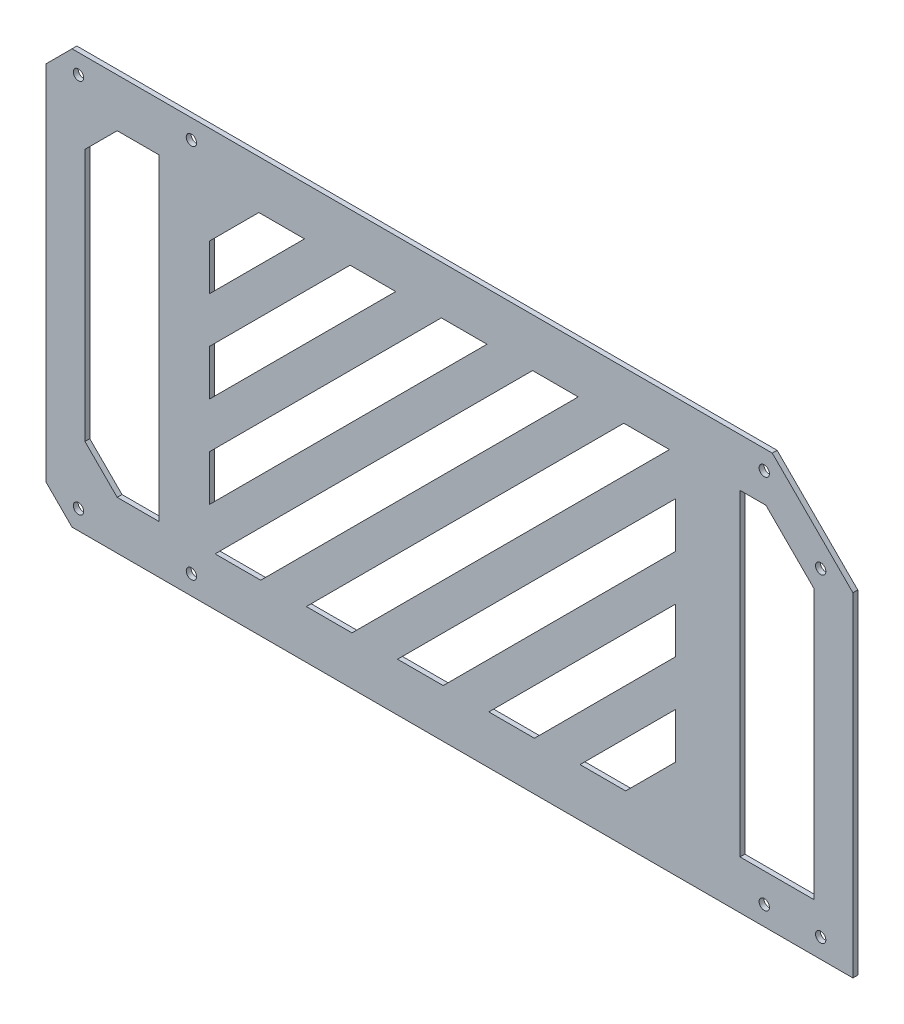
SolidWorks part; units mm, degrees
material "Thornel Mat VMA"
ref_plane "Front Plane" through (0, 0, 0) normal (0, 0, 1) x (1, 0, 0)
ref_plane "Top Plane" through (0, 0, 0) normal (0, 1, 0) x (1, 0, 0)
ref_plane "Right Plane" through (0, 0, 0) normal (1, 0, 0) x (0, 0, -1)
sketch "Sketch2" plane through (0, 0, 0) normal (0, 0, 1) x (1, 0, 0)
  line L0 (613.414, 102.9147) -> (613.414, 4.5) construction
  line L1 (613.414, 4.5) -> (600.414, 4.5) construction
  line L2 (600.414, 4.5) -> (590.414, 14.5) construction
  line L3 (590.414, 14.5) -> (590.414, 92.9147) construction
  line L4 (590.414, 92.9147) -> (600.414, 102.9147) construction
  line L5 (600.414, 102.9147) -> (613.414, 102.9147) construction
  line L6 (613.414, 102.9147) -> (613.414, 4.5)
  line L7 (613.414, 4.5) -> (600.414, 4.5)
  line L8 (600.414, 4.5) -> (590.414, 14.5)
  line L9 (785.4778, 117.9147) -> (785.4778, 2.5)
  line L10 (627.4379, 2.9147) -> (627.4379, 117.9147)
  line L11 (627.4379, 117.9147) -> (586.414, 117.9147)
  line L12 (586.414, 117.9147) -> (578.414, 109.9147)
  line L13 (578.414, 109.9147) -> (578.414, -2.5)
  line L14 (578.414, -2.5) -> (586.414, -10.5)
  line L15 (586.414, -10.5) -> (627.4379, -10.5)
  line L16 (627.4379, -10.5) -> (627.4379, 0)
  line L17 (627.4379, 0) -> (598.414, 0)
  line L18 (598.414, 0) -> (598.414, 2.9147)
  line L19 (598.414, 2.9147) -> (627.4379, 2.9147)
  line L21 (803.4778, 117.9147) -> (586.414, 117.9147)
  line L22 (586.414, 117.9147) -> (578.414, 109.9147)
  line L23 (578.414, 109.9147) -> (578.414, -2.5)
  line L24 (578.414, -2.5) -> (586.414, -10.5)
  line L25 (586.414, -10.5) -> (828.4778, -10.5)
  line L30 (785.4778, 2.5) -> (823.4778, 2.5)
  line L31 (823.4778, 2.5) -> (823.4778, 0)
  line L32 (823.4778, 0) -> (798.4778, 0)
  line L33 (798.4778, 0) -> (798.4778, -10.5)
  line L34 (798.4778, -10.5) -> (828.4778, -10.5)
  line L35 (828.4778, -10.5) -> (828.4778, 92.9147)
  line L36 (828.4778, 92.9147) -> (803.4778, 117.9147)
  line L37 (803.4778, 117.9147) -> (785.4778, 117.9147)
  line L44 (828.4778, -10.5) -> (828.4778, 92.9147)
  line L45 (828.4778, 92.9147) -> (803.4778, 117.9147)
  line L47 (590.414, 14.5) -> (590.414, 92.9147)
  line L48 (590.414, 92.9147) -> (600.414, 102.9147)
  line L49 (600.414, 102.9147) -> (613.414, 102.9147)
  line L50 (793.4778, 4.5) -> (816.4778, 4.5) construction
  line L51 (816.4778, 4.5) -> (816.4778, 87.9442) construction
  line L52 (816.4778, 87.9442) -> (801.5072, 102.9147) construction
  line L54 (801.5072, 102.9147) -> (793.4778, 102.9147) construction
  line L55 (793.4778, 4.5) -> (816.4778, 4.5)
  line L56 (816.4778, 4.5) -> (816.4778, 87.9442)
  line L57 (816.4778, 87.9442) -> (801.5072, 102.9147)
  line L58 (793.4778, 102.9147) -> (793.4778, 4.5)
  line L59 (801.5072, 102.9147) -> (793.4778, 102.9147)
  dimension "D1" = 0
  dimension "D2" = 0
extrude "Boss-Extrude1" add sketch "Sketch2" along normal blind 1.5
sketch "Sketch3" plane through (0, 0, 1.5) normal (0, 0, 1) x (1, 0, 0)
  line L0 (655.29, 102.9147) -> (633.414, 102.9147)
  line L5 (633.414, 102.9147) -> (633.414, 65.0245)
  line L6 (633.414, 27.1342) -> (633.414, 4.5)
  line L7 (633.414, 4.5) -> (642.2221, 4.5)
  line L43 (793.5072, 4.5) -> (808.4778, 4.5) construction
  line L44 (633.414, 102.9147) -> (773.4778, 102.9147) construction
  line L45 (633.414, 102.9147) -> (633.414, 4.5) construction
  line L46 (633.414, 4.5) -> (773.4778, 4.5) construction
  line L47 (773.4778, 102.9147) -> (773.4778, 4.5) construction
  line L48 (801.5072, 102.9147) -> (793.4778, 102.9147) construction
  line L49 (793.4778, 102.9147) -> (793.4778, 95.9442) construction
  line L50 (613.414, 4.5) -> (613.414, 102.9147) construction
  line L51 (655.29, 102.9147) -> (633.414, 65.0245)
  line L52 (677.1659, 102.9147) -> (633.414, 27.1342)
  line L53 (699.0418, 102.9147) -> (642.2221, 4.5)
  line L54 (720.9178, 102.9147) -> (664.098, 4.5)
  line L55 (742.7937, 102.9147) -> (685.974, 4.5)
  line L56 (764.6697, 102.9147) -> (707.8499, 4.5)
  line L57 (773.4778, 80.2805) -> (729.7259, 4.5)
  line L58 (773.4778, 42.3903) -> (751.6018, 4.5)
  line L59 (664.098, 4.5) -> (685.974, 4.5)
  line L60 (707.8499, 4.5) -> (729.7259, 4.5)
  line L61 (751.6018, 4.5) -> (773.4778, 4.5)
  line L62 (773.4778, 4.5) -> (773.4778, 42.3903)
  line L63 (773.4778, 80.2805) -> (773.4778, 102.9147)
  line L64 (773.4778, 102.9147) -> (764.6697, 102.9147)
  line L65 (742.7937, 102.9147) -> (720.9178, 102.9147)
  line L66 (699.0418, 102.9147) -> (677.1659, 102.9147)
  line L67 (655.29, 102.9147) -> (677.1659, 102.9147) construction
  line L68 (699.0418, 102.9147) -> (720.9178, 102.9147) construction
  line L69 (685.974, 4.5) -> (707.8499, 4.5) construction
  line L70 (729.7259, 4.5) -> (751.6018, 4.5) construction
  dimension "D1" = 20
  dimension "D2" = 20
  dimension "D3" = 60
sketch "Sketch4" plane through (0, 0, 1.5) normal (0, 0, 1) x (1, 0, 0)
  line L0 (613.414, 102.9147) -> (600.414, 102.9147) construction
  line L1 (633.414, 102.9147) -> (773.4778, 102.9147) construction
  line L2 (633.414, 102.9147) -> (633.414, 4.5) construction
  line L3 (633.414, 4.5) -> (773.4778, 4.5) construction
  line L4 (773.4778, 102.9147) -> (773.4778, 4.5) construction
  line L5 (600.414, 4.5) -> (613.414, 4.5) construction
  line L6 (613.414, 4.5) -> (613.414, 102.9147) construction
  line L8 (697.4459, 94.072) -> (694.4459, 99.2681)
  line L9 (649.1565, 94.072) -> (646.1565, 99.2681)
  line L10 (646.1565, 99.2681) -> (640.1565, 99.2681)
  line L11 (640.1565, 99.2681) -> (637.1565, 94.072)
  line L12 (637.1565, 94.072) -> (640.1565, 88.8758)
  line L13 (640.1565, 88.8758) -> (646.1565, 88.8758)
  line L14 (646.1565, 88.8758) -> (649.1565, 94.072)
  line L15 (673.1565, 94.072) -> (670.1565, 99.2681)
  line L16 (670.1565, 99.2681) -> (664.1565, 99.2681)
  line L17 (664.1565, 99.2681) -> (661.1565, 94.072)
  line L18 (661.1565, 94.072) -> (664.1565, 88.8758)
  line L19 (664.1565, 88.8758) -> (670.1565, 88.8758)
  line L20 (670.1565, 88.8758) -> (673.1565, 94.072)
  line L21 (661.1565, 83.6797) -> (658.1565, 88.8758)
  line L22 (658.1565, 88.8758) -> (652.1565, 88.8758)
  line L23 (652.1565, 88.8758) -> (649.1565, 83.6797)
  line L24 (649.1565, 83.6797) -> (652.1565, 78.4835)
  line L25 (652.1565, 78.4835) -> (658.1565, 78.4835)
  line L26 (658.1565, 78.4835) -> (661.1565, 83.6797)
  line L27 (685.1565, 83.6797) -> (682.1565, 88.8758)
  line L28 (682.1565, 88.8758) -> (676.1565, 88.8758)
  line L29 (676.1565, 88.8758) -> (673.1565, 83.6797)
  line L30 (673.1565, 83.6797) -> (676.1565, 78.4835)
  line L31 (676.1565, 78.4835) -> (682.1565, 78.4835)
  line L32 (682.1565, 78.4835) -> (685.1565, 83.6797)
  line L33 (694.4459, 99.2681) -> (688.4459, 99.2681)
  line L34 (688.4459, 99.2681) -> (685.4459, 94.072)
  line L35 (685.4459, 94.072) -> (688.4459, 88.8758)
  line L36 (688.4459, 88.8758) -> (694.4459, 88.8758)
  line L37 (694.4459, 88.8758) -> (697.4459, 94.072)
  line L38 (721.4459, 94.072) -> (718.4459, 99.2681)
  line L39 (718.4459, 99.2681) -> (712.4459, 99.2681)
  line L40 (712.4459, 99.2681) -> (709.4459, 94.072)
  line L41 (709.4459, 94.072) -> (712.4459, 88.8758)
  line L42 (712.4459, 88.8758) -> (718.4459, 88.8758)
  line L43 (718.4459, 88.8758) -> (721.4459, 94.072)
  line L44 (709.4459, 83.6797) -> (706.4459, 88.8758)
  line L45 (706.4459, 88.8758) -> (700.4459, 88.8758)
  line L46 (700.4459, 88.8758) -> (697.4459, 83.6797)
  line L47 (697.4459, 83.6797) -> (700.4459, 78.4835)
  line L48 (700.4459, 78.4835) -> (706.4459, 78.4835)
  line L49 (706.4459, 78.4835) -> (709.4459, 83.6797)
  line L50 (733.4459, 83.6797) -> (730.4459, 88.8758)
  line L51 (730.4459, 88.8758) -> (724.4459, 88.8758)
  line L52 (724.4459, 88.8758) -> (721.4459, 83.6797)
  line L53 (721.4459, 83.6797) -> (724.4459, 78.4835)
  line L54 (724.4459, 78.4835) -> (730.4459, 78.4835)
  line L55 (730.4459, 78.4835) -> (733.4459, 83.6797)
  line L56 (745.7353, 94.072) -> (742.7353, 99.2681)
  line L57 (742.7353, 99.2681) -> (736.7353, 99.2681)
  line L58 (736.7353, 99.2681) -> (733.7353, 94.072)
  line L59 (733.7353, 94.072) -> (736.7353, 88.8758)
  line L60 (736.7353, 88.8758) -> (742.7353, 88.8758)
  line L61 (742.7353, 88.8758) -> (745.7353, 94.072)
  line L62 (769.7353, 94.072) -> (766.7353, 99.2681)
  line L63 (766.7353, 99.2681) -> (760.7353, 99.2681)
  line L64 (760.7353, 99.2681) -> (757.7353, 94.072)
  line L65 (757.7353, 94.072) -> (760.7353, 88.8758)
  line L66 (760.7353, 88.8758) -> (766.7353, 88.8758)
  line L67 (766.7353, 88.8758) -> (769.7353, 94.072)
  line L68 (757.7353, 83.6797) -> (754.7353, 88.8758)
  line L69 (754.7353, 88.8758) -> (748.7353, 88.8758)
  line L70 (748.7353, 88.8758) -> (745.7353, 83.6797)
  line L71 (745.7353, 83.6797) -> (748.7353, 78.4835)
  line L72 (748.7353, 78.4835) -> (754.7353, 78.4835)
  line L73 (754.7353, 78.4835) -> (757.7353, 83.6797)
  line L104 (697.4459, 73.8897) -> (694.4459, 79.0858)
  line L105 (694.4459, 79.0858) -> (688.4459, 79.0858)
  line L106 (688.4459, 79.0858) -> (685.4459, 73.8897)
  line L107 (685.4459, 73.8897) -> (688.4459, 68.6935)
  line L108 (688.4459, 68.6935) -> (694.4459, 68.6935)
  line L109 (694.4459, 68.6935) -> (697.4459, 73.8897)
  line L110 (721.4459, 73.8897) -> (718.4459, 79.0858)
  line L111 (718.4459, 79.0858) -> (712.4459, 79.0858)
  line L112 (712.4459, 79.0858) -> (709.4459, 73.8897)
  line L113 (709.4459, 73.8897) -> (712.4459, 68.6935)
  line L114 (712.4459, 68.6935) -> (718.4459, 68.6935)
  line L115 (718.4459, 68.6935) -> (721.4459, 73.8897)
  line L116 (709.4459, 63.4974) -> (706.4459, 68.6935)
  line L117 (706.4459, 68.6935) -> (700.4459, 68.6935)
  line L118 (700.4459, 68.6935) -> (697.4459, 63.4974)
  line L119 (697.4459, 63.4974) -> (700.4459, 58.3012)
  line L120 (700.4459, 58.3012) -> (706.4459, 58.3012)
  line L121 (706.4459, 58.3012) -> (709.4459, 63.4974)
  line L122 (733.4459, 63.4974) -> (730.4459, 68.6935)
  line L123 (730.4459, 68.6935) -> (724.4459, 68.6935)
  line L124 (724.4459, 68.6935) -> (721.4459, 63.4974)
  line L125 (721.4459, 63.4974) -> (724.4459, 58.3012)
  line L126 (724.4459, 58.3012) -> (730.4459, 58.3012)
  line L127 (730.4459, 58.3012) -> (733.4459, 63.4974)
  line L128 (745.7353, 73.8897) -> (742.7353, 79.0858)
  line L129 (742.7353, 79.0858) -> (736.7353, 79.0858)
  line L130 (736.7353, 79.0858) -> (733.7353, 73.8897)
  line L131 (733.7353, 73.8897) -> (736.7353, 68.6935)
  line L132 (736.7353, 68.6935) -> (742.7353, 68.6935)
  line L133 (742.7353, 68.6935) -> (745.7353, 73.8897)
  line L134 (769.7353, 73.8897) -> (766.7353, 79.0858)
  line L135 (766.7353, 79.0858) -> (760.7353, 79.0858)
  line L136 (760.7353, 79.0858) -> (757.7353, 73.8897)
  line L137 (757.7353, 73.8897) -> (760.7353, 68.6935)
  line L138 (760.7353, 68.6935) -> (766.7353, 68.6935)
  line L139 (766.7353, 68.6935) -> (769.7353, 73.8897)
  line L140 (757.7353, 63.4974) -> (754.7353, 68.6935)
  line L141 (754.7353, 68.6935) -> (748.7353, 68.6935)
  line L142 (748.7353, 68.6935) -> (745.7353, 63.4974)
  line L143 (745.7353, 63.4974) -> (748.7353, 58.3012)
  line L144 (748.7353, 58.3012) -> (754.7353, 58.3012)
  line L145 (754.7353, 58.3012) -> (757.7353, 63.4974)
  line L176 (697.4459, 53.7074) -> (694.4459, 58.9035)
  line L177 (694.4459, 58.9035) -> (688.4459, 58.9035)
  line L178 (688.4459, 58.9035) -> (685.4459, 53.7074)
  line L179 (685.4459, 53.7074) -> (688.4459, 48.5112)
  line L180 (688.4459, 48.5112) -> (694.4459, 48.5112)
  line L181 (694.4459, 48.5112) -> (697.4459, 53.7074)
  line L182 (721.4459, 53.7074) -> (718.4459, 58.9035)
  line L183 (718.4459, 58.9035) -> (712.4459, 58.9035)
  line L184 (712.4459, 58.9035) -> (709.4459, 53.7074)
  line L185 (709.4459, 53.7074) -> (712.4459, 48.5112)
  line L186 (712.4459, 48.5112) -> (718.4459, 48.5112)
  line L187 (718.4459, 48.5112) -> (721.4459, 53.7074)
  line L188 (709.4459, 43.3151) -> (706.4459, 48.5112)
  line L189 (706.4459, 48.5112) -> (700.4459, 48.5112)
  line L190 (700.4459, 48.5112) -> (697.4459, 43.3151)
  line L191 (697.4459, 43.3151) -> (700.4459, 38.1189)
  line L192 (700.4459, 38.1189) -> (706.4459, 38.1189)
  line L193 (706.4459, 38.1189) -> (709.4459, 43.3151)
  line L194 (733.4459, 43.3151) -> (730.4459, 48.5112)
  line L195 (730.4459, 48.5112) -> (724.4459, 48.5112)
  line L196 (724.4459, 48.5112) -> (721.4459, 43.3151)
  line L197 (721.4459, 43.3151) -> (724.4459, 38.1189)
  line L198 (724.4459, 38.1189) -> (730.4459, 38.1189)
  line L199 (730.4459, 38.1189) -> (733.4459, 43.3151)
  line L200 (745.7353, 53.7074) -> (742.7353, 58.9035)
  line L201 (742.7353, 58.9035) -> (736.7353, 58.9035)
  line L202 (736.7353, 58.9035) -> (733.7353, 53.7074)
  line L203 (733.7353, 53.7074) -> (736.7353, 48.5112)
  line L204 (736.7353, 48.5112) -> (742.7353, 48.5112)
  line L205 (742.7353, 48.5112) -> (745.7353, 53.7074)
  line L206 (769.7353, 53.7074) -> (766.7353, 58.9035)
  line L207 (766.7353, 58.9035) -> (760.7353, 58.9035)
  line L208 (760.7353, 58.9035) -> (757.7353, 53.7074)
  line L209 (757.7353, 53.7074) -> (760.7353, 48.5112)
  line L210 (760.7353, 48.5112) -> (766.7353, 48.5112)
  line L211 (766.7353, 48.5112) -> (769.7353, 53.7074)
  line L212 (757.7353, 43.3151) -> (754.7353, 48.5112)
  line L213 (754.7353, 48.5112) -> (748.7353, 48.5112)
  line L214 (748.7353, 48.5112) -> (745.7353, 43.3151)
  line L215 (745.7353, 43.3151) -> (748.7353, 38.1189)
  line L216 (748.7353, 38.1189) -> (754.7353, 38.1189)
  line L217 (754.7353, 38.1189) -> (757.7353, 43.3151)
  line L248 (697.4459, 33.5251) -> (694.4459, 38.7212)
  line L249 (694.4459, 38.7212) -> (688.4459, 38.7212)
  line L250 (688.4459, 38.7212) -> (685.4459, 33.5251)
  line L251 (685.4459, 33.5251) -> (688.4459, 28.3289)
  line L252 (688.4459, 28.3289) -> (694.4459, 28.3289)
  line L253 (694.4459, 28.3289) -> (697.4459, 33.5251)
  line L254 (721.4459, 33.5251) -> (718.4459, 38.7212)
  line L255 (718.4459, 38.7212) -> (712.4459, 38.7212)
  line L256 (712.4459, 38.7212) -> (709.4459, 33.5251)
  line L257 (709.4459, 33.5251) -> (712.4459, 28.3289)
  line L258 (712.4459, 28.3289) -> (718.4459, 28.3289)
  line L259 (718.4459, 28.3289) -> (721.4459, 33.5251)
  line L260 (709.4459, 23.1328) -> (706.4459, 28.3289)
  line L261 (706.4459, 28.3289) -> (700.4459, 28.3289)
  line L262 (700.4459, 28.3289) -> (697.4459, 23.1328)
  line L263 (697.4459, 23.1328) -> (700.4459, 17.9366)
  line L264 (700.4459, 17.9366) -> (706.4459, 17.9366)
  line L265 (706.4459, 17.9366) -> (709.4459, 23.1328)
  line L266 (733.4459, 23.1328) -> (730.4459, 28.3289)
  line L267 (730.4459, 28.3289) -> (724.4459, 28.3289)
  line L268 (724.4459, 28.3289) -> (721.4459, 23.1328)
  line L269 (721.4459, 23.1328) -> (724.4459, 17.9366)
  line L270 (724.4459, 17.9366) -> (730.4459, 17.9366)
  line L271 (730.4459, 17.9366) -> (733.4459, 23.1328)
  line L272 (745.7353, 33.5251) -> (742.7353, 38.7212)
  line L273 (742.7353, 38.7212) -> (736.7353, 38.7212)
  line L274 (736.7353, 38.7212) -> (733.7353, 33.5251)
  line L275 (733.7353, 33.5251) -> (736.7353, 28.3289)
  line L276 (736.7353, 28.3289) -> (742.7353, 28.3289)
  line L277 (742.7353, 28.3289) -> (745.7353, 33.5251)
  line L278 (769.7353, 33.5251) -> (766.7353, 38.7212)
  line L279 (766.7353, 38.7212) -> (760.7353, 38.7212)
  line L280 (760.7353, 38.7212) -> (757.7353, 33.5251)
  line L281 (757.7353, 33.5251) -> (760.7353, 28.3289)
  line L282 (760.7353, 28.3289) -> (766.7353, 28.3289)
  line L283 (766.7353, 28.3289) -> (769.7353, 33.5251)
  line L284 (757.7353, 23.1328) -> (754.7353, 28.3289)
  line L285 (754.7353, 28.3289) -> (748.7353, 28.3289)
  line L286 (748.7353, 28.3289) -> (745.7353, 23.1328)
  line L287 (745.7353, 23.1328) -> (748.7353, 17.9366)
  line L288 (748.7353, 17.9366) -> (754.7353, 17.9366)
  line L289 (754.7353, 17.9366) -> (757.7353, 23.1328)
  line L320 (697.4459, 13.3427) -> (694.4459, 18.5389)
  line L321 (694.4459, 18.5389) -> (688.4459, 18.5389)
  line L322 (688.4459, 18.5389) -> (685.4459, 13.3427)
  line L323 (685.4459, 13.3427) -> (688.4459, 8.1466)
  line L324 (688.4459, 8.1466) -> (694.4459, 8.1466)
  line L325 (694.4459, 8.1466) -> (697.4459, 13.3427)
  line L326 (721.4459, 13.3427) -> (718.4459, 18.5389)
  line L327 (718.4459, 18.5389) -> (712.4459, 18.5389)
  line L328 (712.4459, 18.5389) -> (709.4459, 13.3427)
  line L329 (709.4459, 13.3427) -> (712.4459, 8.1466)
  line L330 (712.4459, 8.1466) -> (718.4459, 8.1466)
  line L331 (718.4459, 8.1466) -> (721.4459, 13.3427)
  line L344 (745.7353, 13.3427) -> (742.7353, 18.5389)
  line L345 (742.7353, 18.5389) -> (736.7353, 18.5389)
  line L346 (736.7353, 18.5389) -> (733.7353, 13.3427)
  line L347 (733.7353, 13.3427) -> (736.7353, 8.1466)
  line L348 (736.7353, 8.1466) -> (742.7353, 8.1466)
  line L349 (742.7353, 8.1466) -> (745.7353, 13.3427)
  line L350 (769.7353, 13.3427) -> (766.7353, 18.5389)
  line L351 (766.7353, 18.5389) -> (760.7353, 18.5389)
  line L352 (760.7353, 18.5389) -> (757.7353, 13.3427)
  line L353 (757.7353, 13.3427) -> (760.7353, 8.1466)
  line L354 (760.7353, 8.1466) -> (766.7353, 8.1466)
  line L355 (766.7353, 8.1466) -> (769.7353, 13.3427)
  line L464 (649.1565, 73.8897) -> (646.1565, 79.0858)
  line L465 (646.1565, 79.0858) -> (640.1565, 79.0858)
  line L466 (640.1565, 79.0858) -> (637.1565, 73.8897)
  line L467 (637.1565, 73.8897) -> (640.1565, 68.6935)
  line L468 (640.1565, 68.6935) -> (646.1565, 68.6935)
  line L469 (646.1565, 68.6935) -> (649.1565, 73.8897)
  line L470 (673.1565, 73.8897) -> (670.1565, 79.0858)
  line L471 (670.1565, 79.0858) -> (664.1565, 79.0858)
  line L472 (664.1565, 79.0858) -> (661.1565, 73.8897)
  line L473 (661.1565, 73.8897) -> (664.1565, 68.6935)
  line L474 (664.1565, 68.6935) -> (670.1565, 68.6935)
  line L475 (670.1565, 68.6935) -> (673.1565, 73.8897)
  line L476 (661.1565, 63.4974) -> (658.1565, 68.6935)
  line L477 (658.1565, 68.6935) -> (652.1565, 68.6935)
  line L478 (652.1565, 68.6935) -> (649.1565, 63.4974)
  line L479 (649.1565, 63.4974) -> (652.1565, 58.3012)
  line L480 (652.1565, 58.3012) -> (658.1565, 58.3012)
  line L481 (658.1565, 58.3012) -> (661.1565, 63.4974)
  line L482 (685.1565, 63.4974) -> (682.1565, 68.6935)
  line L483 (682.1565, 68.6935) -> (676.1565, 68.6935)
  line L484 (676.1565, 68.6935) -> (673.1565, 63.4974)
  line L485 (673.1565, 63.4974) -> (676.1565, 58.3012)
  line L486 (676.1565, 58.3012) -> (682.1565, 58.3012)
  line L487 (682.1565, 58.3012) -> (685.1565, 63.4974)
  line L488 (649.1565, 53.7074) -> (646.1565, 58.9035)
  line L489 (646.1565, 58.9035) -> (640.1565, 58.9035)
  line L490 (640.1565, 58.9035) -> (637.1565, 53.7074)
  line L491 (637.1565, 53.7074) -> (640.1565, 48.5112)
  line L492 (640.1565, 48.5112) -> (646.1565, 48.5112)
  line L493 (646.1565, 48.5112) -> (649.1565, 53.7074)
  line L494 (673.1565, 53.7074) -> (670.1565, 58.9035)
  line L495 (670.1565, 58.9035) -> (664.1565, 58.9035)
  line L496 (664.1565, 58.9035) -> (661.1565, 53.7074)
  line L497 (661.1565, 53.7074) -> (664.1565, 48.5112)
  line L498 (664.1565, 48.5112) -> (670.1565, 48.5112)
  line L499 (670.1565, 48.5112) -> (673.1565, 53.7074)
  line L500 (661.1565, 43.3151) -> (658.1565, 48.5112)
  line L501 (658.1565, 48.5112) -> (652.1565, 48.5112)
  line L502 (652.1565, 48.5112) -> (649.1565, 43.3151)
  line L503 (649.1565, 43.3151) -> (652.1565, 38.1189)
  line L504 (652.1565, 38.1189) -> (658.1565, 38.1189)
  line L505 (658.1565, 38.1189) -> (661.1565, 43.3151)
  line L506 (685.1565, 43.3151) -> (682.1565, 48.5112)
  line L507 (682.1565, 48.5112) -> (676.1565, 48.5112)
  line L508 (676.1565, 48.5112) -> (673.1565, 43.3151)
  line L509 (673.1565, 43.3151) -> (676.1565, 38.1189)
  line L510 (676.1565, 38.1189) -> (682.1565, 38.1189)
  line L511 (682.1565, 38.1189) -> (685.1565, 43.3151)
  line L512 (649.1565, 33.5251) -> (646.1565, 38.7212)
  line L513 (646.1565, 38.7212) -> (640.1565, 38.7212)
  line L514 (640.1565, 38.7212) -> (637.1565, 33.5251)
  line L515 (637.1565, 33.5251) -> (640.1565, 28.3289)
  line L516 (640.1565, 28.3289) -> (646.1565, 28.3289)
  line L517 (646.1565, 28.3289) -> (649.1565, 33.5251)
  line L518 (673.1565, 33.5251) -> (670.1565, 38.7212)
  line L519 (670.1565, 38.7212) -> (664.1565, 38.7212)
  line L520 (664.1565, 38.7212) -> (661.1565, 33.5251)
  line L521 (661.1565, 33.5251) -> (664.1565, 28.3289)
  line L522 (664.1565, 28.3289) -> (670.1565, 28.3289)
  line L523 (670.1565, 28.3289) -> (673.1565, 33.5251)
  line L524 (661.1565, 23.1328) -> (658.1565, 28.3289)
  line L525 (658.1565, 28.3289) -> (652.1565, 28.3289)
  line L526 (652.1565, 28.3289) -> (649.1565, 23.1328)
  line L527 (649.1565, 23.1328) -> (652.1565, 17.9366)
  line L528 (652.1565, 17.9366) -> (658.1565, 17.9366)
  line L529 (658.1565, 17.9366) -> (661.1565, 23.1328)
  line L530 (685.1565, 23.1328) -> (682.1565, 28.3289)
  line L531 (682.1565, 28.3289) -> (676.1565, 28.3289)
  line L532 (676.1565, 28.3289) -> (673.1565, 23.1328)
  line L533 (673.1565, 23.1328) -> (676.1565, 17.9366)
  line L534 (676.1565, 17.9366) -> (682.1565, 17.9366)
  line L535 (682.1565, 17.9366) -> (685.1565, 23.1328)
  line L536 (649.1565, 13.3427) -> (646.1565, 18.5389)
  line L537 (646.1565, 18.5389) -> (640.1565, 18.5389)
  line L538 (640.1565, 18.5389) -> (637.1565, 13.3427)
  line L539 (637.1565, 13.3427) -> (640.1565, 8.1466)
  line L540 (640.1565, 8.1466) -> (646.1565, 8.1466)
  line L541 (646.1565, 8.1466) -> (649.1565, 13.3427)
  line L542 (673.1565, 13.3427) -> (670.1565, 18.5389)
  line L543 (670.1565, 18.5389) -> (664.1565, 18.5389)
  line L544 (664.1565, 18.5389) -> (661.1565, 13.3427)
  line L545 (661.1565, 13.3427) -> (664.1565, 8.1466)
  line L546 (664.1565, 8.1466) -> (670.1565, 8.1466)
  line L547 (670.1565, 8.1466) -> (673.1565, 13.3427)
  line L584 (781.7353, 83.6797) -> (778.7353, 88.8758) [skipped]
  line L585 (778.7353, 88.8758) -> (772.7353, 88.8758) [skipped]
  line L586 (772.7353, 88.8758) -> (769.7353, 83.6797) [skipped]
  line L587 (769.7353, 83.6797) -> (772.7353, 78.4835) [skipped]
  line L588 (772.7353, 78.4835) -> (778.7353, 78.4835) [skipped]
  line L589 (778.7353, 78.4835) -> (781.7353, 83.6797) [skipped]
  line L590 (794.0247, 94.072) -> (791.0247, 99.2681) [skipped]
  line L591 (791.0247, 99.2681) -> (785.0247, 99.2681) [skipped]
  line L592 (785.0247, 99.2681) -> (782.0247, 94.072) [skipped]
  line L593 (782.0247, 94.072) -> (785.0247, 88.8758) [skipped]
  line L594 (785.0247, 88.8758) -> (791.0247, 88.8758) [skipped]
  line L595 (791.0247, 88.8758) -> (794.0247, 94.072) [skipped]
  line L596 (818.0247, 94.072) -> (815.0247, 99.2681) [skipped]
  line L597 (815.0247, 99.2681) -> (809.0247, 99.2681) [skipped]
  line L598 (809.0247, 99.2681) -> (806.0247, 94.072) [skipped]
  line L599 (806.0247, 94.072) -> (809.0247, 88.8758) [skipped]
  line L600 (809.0247, 88.8758) -> (815.0247, 88.8758) [skipped]
  line L601 (815.0247, 88.8758) -> (818.0247, 94.072) [skipped]
  line L602 (806.0247, 83.6797) -> (803.0247, 88.8758) [skipped]
  line L603 (803.0247, 88.8758) -> (797.0247, 88.8758) [skipped]
  line L604 (797.0247, 88.8758) -> (794.0247, 83.6797) [skipped]
  line L605 (794.0247, 83.6797) -> (797.0247, 78.4835) [skipped]
  line L606 (797.0247, 78.4835) -> (803.0247, 78.4835) [skipped]
  line L607 (803.0247, 78.4835) -> (806.0247, 83.6797) [skipped]
  line L608 (830.0247, 83.6797) -> (827.0247, 88.8758) [skipped]
  line L609 (827.0247, 88.8758) -> (821.0247, 88.8758) [skipped]
  line L610 (821.0247, 88.8758) -> (818.0247, 83.6797) [skipped]
  line L611 (818.0247, 83.6797) -> (821.0247, 78.4835) [skipped]
  line L612 (821.0247, 78.4835) -> (827.0247, 78.4835) [skipped]
  line L613 (827.0247, 78.4835) -> (830.0247, 83.6797) [skipped]
  line L614 (781.7353, 63.4974) -> (778.7353, 68.6935) [skipped]
  line L615 (778.7353, 68.6935) -> (772.7353, 68.6935) [skipped]
  line L616 (772.7353, 68.6935) -> (769.7353, 63.4974) [skipped]
  line L617 (769.7353, 63.4974) -> (772.7353, 58.3012) [skipped]
  line L618 (772.7353, 58.3012) -> (778.7353, 58.3012) [skipped]
  line L619 (778.7353, 58.3012) -> (781.7353, 63.4974) [skipped]
  line L620 (794.0247, 73.8897) -> (791.0247, 79.0858) [skipped]
  line L621 (791.0247, 79.0858) -> (785.0247, 79.0858) [skipped]
  line L622 (785.0247, 79.0858) -> (782.0247, 73.8897) [skipped]
  line L623 (782.0247, 73.8897) -> (785.0247, 68.6935) [skipped]
  line L624 (785.0247, 68.6935) -> (791.0247, 68.6935) [skipped]
  line L625 (791.0247, 68.6935) -> (794.0247, 73.8897) [skipped]
  line L626 (818.0247, 73.8897) -> (815.0247, 79.0858) [skipped]
  line L627 (815.0247, 79.0858) -> (809.0247, 79.0858) [skipped]
  line L628 (809.0247, 79.0858) -> (806.0247, 73.8897) [skipped]
  line L629 (806.0247, 73.8897) -> (809.0247, 68.6935) [skipped]
  line L630 (809.0247, 68.6935) -> (815.0247, 68.6935) [skipped]
  line L631 (815.0247, 68.6935) -> (818.0247, 73.8897) [skipped]
  line L632 (806.0247, 63.4974) -> (803.0247, 68.6935) [skipped]
  line L633 (803.0247, 68.6935) -> (797.0247, 68.6935) [skipped]
  line L634 (797.0247, 68.6935) -> (794.0247, 63.4974) [skipped]
  line L635 (794.0247, 63.4974) -> (797.0247, 58.3012) [skipped]
  line L636 (797.0247, 58.3012) -> (803.0247, 58.3012) [skipped]
  line L637 (803.0247, 58.3012) -> (806.0247, 63.4974) [skipped]
  line L638 (830.0247, 63.4974) -> (827.0247, 68.6935) [skipped]
  line L639 (827.0247, 68.6935) -> (821.0247, 68.6935) [skipped]
  line L640 (821.0247, 68.6935) -> (818.0247, 63.4974) [skipped]
  line L641 (818.0247, 63.4974) -> (821.0247, 58.3012) [skipped]
  line L642 (821.0247, 58.3012) -> (827.0247, 58.3012) [skipped]
  line L643 (827.0247, 58.3012) -> (830.0247, 63.4974) [skipped]
  line L644 (781.7353, 43.3151) -> (778.7353, 48.5112) [skipped]
  line L645 (778.7353, 48.5112) -> (772.7353, 48.5112) [skipped]
  line L646 (772.7353, 48.5112) -> (769.7353, 43.3151) [skipped]
  line L647 (769.7353, 43.3151) -> (772.7353, 38.1189) [skipped]
  line L648 (772.7353, 38.1189) -> (778.7353, 38.1189) [skipped]
  line L649 (778.7353, 38.1189) -> (781.7353, 43.3151) [skipped]
  line L650 (794.0247, 53.7074) -> (791.0247, 58.9035) [skipped]
  line L651 (791.0247, 58.9035) -> (785.0247, 58.9035) [skipped]
  line L652 (785.0247, 58.9035) -> (782.0247, 53.7074) [skipped]
  line L653 (782.0247, 53.7074) -> (785.0247, 48.5112) [skipped]
  line L654 (785.0247, 48.5112) -> (791.0247, 48.5112) [skipped]
  line L655 (791.0247, 48.5112) -> (794.0247, 53.7074) [skipped]
  line L656 (818.0247, 53.7074) -> (815.0247, 58.9035) [skipped]
  line L657 (815.0247, 58.9035) -> (809.0247, 58.9035) [skipped]
  line L658 (809.0247, 58.9035) -> (806.0247, 53.7074) [skipped]
  line L659 (806.0247, 53.7074) -> (809.0247, 48.5112) [skipped]
  line L660 (809.0247, 48.5112) -> (815.0247, 48.5112) [skipped]
  line L661 (815.0247, 48.5112) -> (818.0247, 53.7074) [skipped]
  line L662 (806.0247, 43.3151) -> (803.0247, 48.5112) [skipped]
  line L663 (803.0247, 48.5112) -> (797.0247, 48.5112) [skipped]
  line L664 (797.0247, 48.5112) -> (794.0247, 43.3151) [skipped]
  line L665 (794.0247, 43.3151) -> (797.0247, 38.1189) [skipped]
  line L666 (797.0247, 38.1189) -> (803.0247, 38.1189) [skipped]
  line L667 (803.0247, 38.1189) -> (806.0247, 43.3151) [skipped]
  line L668 (830.0247, 43.3151) -> (827.0247, 48.5112) [skipped]
  line L669 (827.0247, 48.5112) -> (821.0247, 48.5112) [skipped]
  line L670 (821.0247, 48.5112) -> (818.0247, 43.3151) [skipped]
  line L671 (818.0247, 43.3151) -> (821.0247, 38.1189) [skipped]
  line L672 (821.0247, 38.1189) -> (827.0247, 38.1189) [skipped]
  line L673 (827.0247, 38.1189) -> (830.0247, 43.3151) [skipped]
  line L674 (781.7353, 23.1328) -> (778.7353, 28.3289) [skipped]
  line L675 (778.7353, 28.3289) -> (772.7353, 28.3289) [skipped]
  line L676 (772.7353, 28.3289) -> (769.7353, 23.1328) [skipped]
  line L677 (769.7353, 23.1328) -> (772.7353, 17.9366) [skipped]
  line L678 (772.7353, 17.9366) -> (778.7353, 17.9366) [skipped]
  line L679 (778.7353, 17.9366) -> (781.7353, 23.1328) [skipped]
  line L680 (794.0247, 33.5251) -> (791.0247, 38.7212) [skipped]
  line L681 (791.0247, 38.7212) -> (785.0247, 38.7212) [skipped]
  line L682 (785.0247, 38.7212) -> (782.0247, 33.5251) [skipped]
  line L683 (782.0247, 33.5251) -> (785.0247, 28.3289) [skipped]
  line L684 (785.0247, 28.3289) -> (791.0247, 28.3289) [skipped]
  line L685 (791.0247, 28.3289) -> (794.0247, 33.5251) [skipped]
  line L686 (818.0247, 33.5251) -> (815.0247, 38.7212) [skipped]
  line L687 (815.0247, 38.7212) -> (809.0247, 38.7212) [skipped]
  line L688 (809.0247, 38.7212) -> (806.0247, 33.5251) [skipped]
  line L689 (806.0247, 33.5251) -> (809.0247, 28.3289) [skipped]
  line L690 (809.0247, 28.3289) -> (815.0247, 28.3289) [skipped]
  line L691 (815.0247, 28.3289) -> (818.0247, 33.5251) [skipped]
  line L692 (806.0247, 23.1328) -> (803.0247, 28.3289) [skipped]
  line L693 (803.0247, 28.3289) -> (797.0247, 28.3289) [skipped]
  line L694 (797.0247, 28.3289) -> (794.0247, 23.1328) [skipped]
  line L695 (794.0247, 23.1328) -> (797.0247, 17.9366) [skipped]
  line L696 (797.0247, 17.9366) -> (803.0247, 17.9366) [skipped]
  line L697 (803.0247, 17.9366) -> (806.0247, 23.1328) [skipped]
  line L698 (830.0247, 23.1328) -> (827.0247, 28.3289) [skipped]
  line L699 (827.0247, 28.3289) -> (821.0247, 28.3289) [skipped]
  line L700 (821.0247, 28.3289) -> (818.0247, 23.1328) [skipped]
  line L701 (818.0247, 23.1328) -> (821.0247, 17.9366) [skipped]
  line L702 (821.0247, 17.9366) -> (827.0247, 17.9366) [skipped]
  line L703 (827.0247, 17.9366) -> (830.0247, 23.1328) [skipped]
  line L704 (781.7353, 2.9504) -> (778.7353, 8.1466) [skipped]
  line L705 (778.7353, 8.1466) -> (772.7353, 8.1466) [skipped]
  line L706 (772.7353, 8.1466) -> (769.7353, 2.9504) [skipped]
  line L707 (769.7353, 2.9504) -> (772.7353, -2.2457) [skipped]
  line L708 (772.7353, -2.2457) -> (778.7353, -2.2457) [skipped]
  line L709 (778.7353, -2.2457) -> (781.7353, 2.9504) [skipped]
  line L710 (794.0247, 13.3427) -> (791.0247, 18.5389) [skipped]
  line L711 (791.0247, 18.5389) -> (785.0247, 18.5389) [skipped]
  line L712 (785.0247, 18.5389) -> (782.0247, 13.3427) [skipped]
  line L713 (782.0247, 13.3427) -> (785.0247, 8.1466) [skipped]
  line L714 (785.0247, 8.1466) -> (791.0247, 8.1466) [skipped]
  line L715 (791.0247, 8.1466) -> (794.0247, 13.3427) [skipped]
  line L716 (818.0247, 13.3427) -> (815.0247, 18.5389) [skipped]
  line L717 (815.0247, 18.5389) -> (809.0247, 18.5389) [skipped]
  line L718 (809.0247, 18.5389) -> (806.0247, 13.3427) [skipped]
  line L719 (806.0247, 13.3427) -> (809.0247, 8.1466) [skipped]
  line L720 (809.0247, 8.1466) -> (815.0247, 8.1466) [skipped]
  line L721 (815.0247, 8.1466) -> (818.0247, 13.3427) [skipped]
  line L722 (806.0247, 2.9504) -> (803.0247, 8.1466) [skipped]
  line L723 (803.0247, 8.1466) -> (797.0247, 8.1466) [skipped]
  line L724 (797.0247, 8.1466) -> (794.0247, 2.9504) [skipped]
  line L725 (794.0247, 2.9504) -> (797.0247, -2.2457) [skipped]
  line L726 (797.0247, -2.2457) -> (803.0247, -2.2457) [skipped]
  line L727 (803.0247, -2.2457) -> (806.0247, 2.9504) [skipped]
  line L728 (830.0247, 2.9504) -> (827.0247, 8.1466) [skipped]
  line L729 (827.0247, 8.1466) -> (821.0247, 8.1466) [skipped]
  line L730 (821.0247, 8.1466) -> (818.0247, 2.9504) [skipped]
  line L731 (818.0247, 2.9504) -> (821.0247, -2.2457) [skipped]
  line L732 (821.0247, -2.2457) -> (827.0247, -2.2457) [skipped]
  line L733 (827.0247, -2.2457) -> (830.0247, 2.9504) [skipped]
  line L734 (781.7353, -17.2319) -> (778.7353, -12.0357) [skipped]
  line L735 (778.7353, -12.0357) -> (772.7353, -12.0357) [skipped]
  line L736 (772.7353, -12.0357) -> (769.7353, -17.2319) [skipped]
  line L737 (769.7353, -17.2319) -> (772.7353, -22.428) [skipped]
  line L738 (772.7353, -22.428) -> (778.7353, -22.428) [skipped]
  line L739 (778.7353, -22.428) -> (781.7353, -17.2319) [skipped]
  line L740 (794.0247, -6.8396) -> (791.0247, -1.6434) [skipped]
  line L741 (791.0247, -1.6434) -> (785.0247, -1.6434) [skipped]
  line L742 (785.0247, -1.6434) -> (782.0247, -6.8396) [skipped]
  line L743 (782.0247, -6.8396) -> (785.0247, -12.0357) [skipped]
  line L744 (785.0247, -12.0357) -> (791.0247, -12.0357) [skipped]
  line L745 (791.0247, -12.0357) -> (794.0247, -6.8396) [skipped]
  line L746 (818.0247, -6.8396) -> (815.0247, -1.6434) [skipped]
  line L747 (815.0247, -1.6434) -> (809.0247, -1.6434) [skipped]
  line L748 (809.0247, -1.6434) -> (806.0247, -6.8396) [skipped]
  line L749 (806.0247, -6.8396) -> (809.0247, -12.0357) [skipped]
  line L750 (809.0247, -12.0357) -> (815.0247, -12.0357) [skipped]
  line L751 (815.0247, -12.0357) -> (818.0247, -6.8396) [skipped]
  line L752 (806.0247, -17.2319) -> (803.0247, -12.0357) [skipped]
  line L753 (803.0247, -12.0357) -> (797.0247, -12.0357) [skipped]
  line L754 (797.0247, -12.0357) -> (794.0247, -17.2319) [skipped]
  line L755 (794.0247, -17.2319) -> (797.0247, -22.428) [skipped]
  line L756 (797.0247, -22.428) -> (803.0247, -22.428) [skipped]
  line L757 (803.0247, -22.428) -> (806.0247, -17.2319) [skipped]
  line L758 (830.0247, -17.2319) -> (827.0247, -12.0357) [skipped]
  line L759 (827.0247, -12.0357) -> (821.0247, -12.0357) [skipped]
  line L760 (821.0247, -12.0357) -> (818.0247, -17.2319) [skipped]
  line L761 (818.0247, -17.2319) -> (821.0247, -22.428) [skipped]
  line L762 (821.0247, -22.428) -> (827.0247, -22.428) [skipped]
  line L763 (827.0247, -22.428) -> (830.0247, -17.2319) [skipped]
  line L764 (709.4459, 2.9504) -> (706.4459, 8.1466) [skipped]
  line L765 (700.4459, 8.1466) -> (697.4459, 2.9504) [skipped]
  line L766 (697.4459, 2.9504) -> (700.4459, -2.2457) [skipped]
  line L767 (700.4459, -2.2457) -> (706.4459, -2.2457) [skipped]
  line L768 (706.4459, -2.2457) -> (709.4459, 2.9504) [skipped]
  line L769 (733.4459, 2.9504) -> (730.4459, 8.1466) [skipped]
  line L770 (724.4459, 8.1466) -> (721.4459, 2.9504) [skipped]
  line L771 (721.4459, 2.9504) -> (724.4459, -2.2457) [skipped]
  line L772 (724.4459, -2.2457) -> (730.4459, -2.2457) [skipped]
  line L773 (730.4459, -2.2457) -> (733.4459, 2.9504) [skipped]
  line L774 (757.7353, 2.9504) -> (754.7353, 8.1466) [skipped]
  line L775 (748.7353, 8.1466) -> (745.7353, 2.9504) [skipped]
  line L776 (745.7353, 2.9504) -> (748.7353, -2.2457) [skipped]
  line L777 (748.7353, -2.2457) -> (754.7353, -2.2457) [skipped]
  line L778 (754.7353, -2.2457) -> (757.7353, 2.9504) [skipped]
  line L779 (697.4459, -6.8396) -> (694.4459, -1.6434) [skipped]
  line L780 (694.4459, -1.6434) -> (688.4459, -1.6434) [skipped]
  line L781 (688.4459, -1.6434) -> (685.4459, -6.8396) [skipped]
  line L782 (685.4459, -6.8396) -> (688.4459, -12.0357) [skipped]
  line L783 (688.4459, -12.0357) -> (694.4459, -12.0357) [skipped]
  line L784 (694.4459, -12.0357) -> (697.4459, -6.8396) [skipped]
  line L785 (721.4459, -6.8396) -> (718.4459, -1.6434) [skipped]
  line L786 (718.4459, -1.6434) -> (712.4459, -1.6434) [skipped]
  line L787 (712.4459, -1.6434) -> (709.4459, -6.8396) [skipped]
  line L788 (709.4459, -6.8396) -> (712.4459, -12.0357) [skipped]
  line L789 (712.4459, -12.0357) -> (718.4459, -12.0357) [skipped]
  line L790 (718.4459, -12.0357) -> (721.4459, -6.8396) [skipped]
  line L791 (709.4459, -17.2319) -> (706.4459, -12.0357) [skipped]
  line L792 (706.4459, -12.0357) -> (700.4459, -12.0357) [skipped]
  line L793 (700.4459, -12.0357) -> (697.4459, -17.2319) [skipped]
  line L794 (697.4459, -17.2319) -> (700.4459, -22.428) [skipped]
  line L795 (700.4459, -22.428) -> (706.4459, -22.428) [skipped]
  line L796 (706.4459, -22.428) -> (709.4459, -17.2319) [skipped]
  line L797 (733.4459, -17.2319) -> (730.4459, -12.0357) [skipped]
  line L798 (730.4459, -12.0357) -> (724.4459, -12.0357) [skipped]
  line L799 (724.4459, -12.0357) -> (721.4459, -17.2319) [skipped]
  line L800 (721.4459, -17.2319) -> (724.4459, -22.428) [skipped]
  line L801 (724.4459, -22.428) -> (730.4459, -22.428) [skipped]
  line L802 (730.4459, -22.428) -> (733.4459, -17.2319) [skipped]
  line L803 (745.7353, -6.8396) -> (742.7353, -1.6434) [skipped]
  line L804 (742.7353, -1.6434) -> (736.7353, -1.6434) [skipped]
  line L805 (736.7353, -1.6434) -> (733.7353, -6.8396) [skipped]
  line L806 (733.7353, -6.8396) -> (736.7353, -12.0357) [skipped]
  line L807 (736.7353, -12.0357) -> (742.7353, -12.0357) [skipped]
  line L808 (742.7353, -12.0357) -> (745.7353, -6.8396) [skipped]
  line L809 (769.7353, -6.8396) -> (766.7353, -1.6434) [skipped]
  line L810 (766.7353, -1.6434) -> (760.7353, -1.6434) [skipped]
  line L811 (760.7353, -1.6434) -> (757.7353, -6.8396) [skipped]
  line L812 (757.7353, -6.8396) -> (760.7353, -12.0357) [skipped]
  line L813 (760.7353, -12.0357) -> (766.7353, -12.0357) [skipped]
  line L814 (766.7353, -12.0357) -> (769.7353, -6.8396) [skipped]
  line L815 (757.7353, -17.2319) -> (754.7353, -12.0357) [skipped]
  line L816 (754.7353, -12.0357) -> (748.7353, -12.0357) [skipped]
  line L817 (748.7353, -12.0357) -> (745.7353, -17.2319) [skipped]
  line L818 (745.7353, -17.2319) -> (748.7353, -22.428) [skipped]
  line L819 (748.7353, -22.428) -> (754.7353, -22.428) [skipped]
  line L820 (754.7353, -22.428) -> (757.7353, -17.2319) [skipped]
  line L821 (661.1565, 2.9504) -> (658.1565, 8.1466) [skipped]
  line L822 (652.1565, 8.1466) -> (649.1565, 2.9504) [skipped]
  line L823 (649.1565, 2.9504) -> (652.1565, -2.2457) [skipped]
  line L824 (652.1565, -2.2457) -> (658.1565, -2.2457) [skipped]
  line L825 (658.1565, -2.2457) -> (661.1565, 2.9504) [skipped]
  line L826 (685.1565, 2.9504) -> (682.1565, 8.1466) [skipped]
  line L827 (676.1565, 8.1466) -> (673.1565, 2.9504) [skipped]
  line L828 (673.1565, 2.9504) -> (676.1565, -2.2457) [skipped]
  line L829 (676.1565, -2.2457) -> (682.1565, -2.2457) [skipped]
  line L830 (682.1565, -2.2457) -> (685.1565, 2.9504) [skipped]
  line L831 (649.1565, -6.8396) -> (646.1565, -1.6434) [skipped]
  line L832 (646.1565, -1.6434) -> (640.1565, -1.6434) [skipped]
  line L833 (640.1565, -1.6434) -> (637.1565, -6.8396) [skipped]
  line L834 (637.1565, -6.8396) -> (640.1565, -12.0357) [skipped]
  line L835 (640.1565, -12.0357) -> (646.1565, -12.0357) [skipped]
  line L836 (646.1565, -12.0357) -> (649.1565, -6.8396) [skipped]
  line L837 (673.1565, -6.8396) -> (670.1565, -1.6434) [skipped]
  line L838 (670.1565, -1.6434) -> (664.1565, -1.6434) [skipped]
  line L839 (664.1565, -1.6434) -> (661.1565, -6.8396) [skipped]
  line L840 (661.1565, -6.8396) -> (664.1565, -12.0357) [skipped]
  line L841 (664.1565, -12.0357) -> (670.1565, -12.0357) [skipped]
  line L842 (670.1565, -12.0357) -> (673.1565, -6.8396) [skipped]
  line L843 (661.1565, -17.2319) -> (658.1565, -12.0357) [skipped]
  line L844 (658.1565, -12.0357) -> (652.1565, -12.0357) [skipped]
  line L845 (652.1565, -12.0357) -> (649.1565, -17.2319) [skipped]
  line L846 (649.1565, -17.2319) -> (652.1565, -22.428) [skipped]
  line L847 (652.1565, -22.428) -> (658.1565, -22.428) [skipped]
  line L848 (658.1565, -22.428) -> (661.1565, -17.2319) [skipped]
  line L849 (685.1565, -17.2319) -> (682.1565, -12.0357) [skipped]
  line L850 (682.1565, -12.0357) -> (676.1565, -12.0357) [skipped]
  line L851 (676.1565, -12.0357) -> (673.1565, -17.2319) [skipped]
  line L852 (673.1565, -17.2319) -> (676.1565, -22.428) [skipped]
  line L853 (676.1565, -22.428) -> (682.1565, -22.428) [skipped]
  line L854 (682.1565, -22.428) -> (685.1565, -17.2319) [skipped]
  line L855 (658.1565, 8.1466) -> (652.1565, 8.1466) [skipped]
  line L856 (682.1565, 8.1466) -> (676.1565, 8.1466) [skipped]
  line L857 (706.4459, 8.1466) -> (700.4459, 8.1466) [skipped]
  line L858 (730.4459, 8.1466) -> (724.4459, 8.1466) [skipped]
  line L859 (754.7353, 8.1466) -> (748.7353, 8.1466) [skipped]
  line L860 (643.1565, 94.072) -> (633.414, 102.9147) construction
  line L861 (763.7353, 94.072) -> (773.4778, 102.9147) construction
  line L862 (763.7353, 13.3427) -> (773.4778, 4.5) construction
  line L863 (643.1565, 13.3427) -> (633.414, 4.5) construction
  line L864 (793.4778, 102.9147) -> (793.4778, 4.5) construction
  circle A0 centre (643.1565, 94.072) radius 5.1962 construction
  circle A1 centre (667.1565, 94.072) radius 5.1962 construction
  circle A2 centre (655.1565, 83.6797) radius 5.1962 construction
  circle A3 centre (679.1565, 83.6797) radius 5.1962 construction
  circle A4 centre (691.4459, 94.072) radius 5.1962 construction
  circle A5 centre (715.4459, 94.072) radius 5.1962 construction
  circle A6 centre (703.4459, 83.6797) radius 5.1962 construction
  circle A7 centre (727.4459, 83.6797) radius 5.1962 construction
  circle A8 centre (739.7353, 94.072) radius 5.1962 construction
  circle A9 centre (763.7353, 94.072) radius 5.1962 construction
  circle A10 centre (751.7353, 83.6797) radius 5.1962 construction
  circle A16 centre (691.4459, 73.8897) radius 5.1962 construction
  circle A17 centre (715.4459, 73.8897) radius 5.1962 construction
  circle A18 centre (703.4459, 63.4974) radius 5.1962 construction
  circle A19 centre (727.4459, 63.4974) radius 5.1962 construction
  circle A20 centre (739.7353, 73.8897) radius 5.1962 construction
  circle A21 centre (763.7353, 73.8897) radius 5.1962 construction
  circle A22 centre (751.7353, 63.4974) radius 5.1962 construction
  circle A28 centre (691.4459, 53.7074) radius 5.1962 construction
  circle A29 centre (715.4459, 53.7074) radius 5.1962 construction
  circle A30 centre (703.4459, 43.3151) radius 5.1962 construction
  circle A31 centre (727.4459, 43.3151) radius 5.1962 construction
  circle A32 centre (739.7353, 53.7074) radius 5.1962 construction
  circle A33 centre (763.7353, 53.7074) radius 5.1962 construction
  circle A34 centre (751.7353, 43.3151) radius 5.1962 construction
  circle A40 centre (691.4459, 33.5251) radius 5.1962 construction
  circle A41 centre (715.4459, 33.5251) radius 5.1962 construction
  circle A42 centre (703.4459, 23.1328) radius 5.1962 construction
  circle A43 centre (727.4459, 23.1328) radius 5.1962 construction
  circle A44 centre (739.7353, 33.5251) radius 5.1962 construction
  circle A45 centre (763.7353, 33.5251) radius 5.1962 construction
  circle A46 centre (751.7353, 23.1328) radius 5.1962 construction
  circle A52 centre (691.4459, 13.3427) radius 5.1962 construction
  circle A53 centre (715.4459, 13.3427) radius 5.1962 construction
  circle A56 centre (739.7353, 13.3427) radius 5.1962 construction
  circle A57 centre (763.7353, 13.3427) radius 5.1962 construction
  circle A76 centre (643.1565, 73.8897) radius 5.1962 construction
  circle A77 centre (667.1565, 73.8897) radius 5.1962 construction
  circle A78 centre (655.1565, 63.4974) radius 5.1962 construction
  circle A79 centre (679.1565, 63.4974) radius 5.1962 construction
  circle A80 centre (643.1565, 53.7074) radius 5.1962 construction
  circle A81 centre (667.1565, 53.7074) radius 5.1962 construction
  circle A82 centre (655.1565, 43.3151) radius 5.1962 construction
  circle A83 centre (679.1565, 43.3151) radius 5.1962 construction
  circle A84 centre (643.1565, 33.5251) radius 5.1962 construction
  circle A85 centre (667.1565, 33.5251) radius 5.1962 construction
  circle A86 centre (655.1565, 23.1328) radius 5.1962 construction
  circle A87 centre (679.1565, 23.1328) radius 5.1962 construction
  circle A88 centre (643.1565, 13.3427) radius 5.1962 construction
  circle A89 centre (667.1565, 13.3427) radius 5.1962 construction
  circle A96 centre (775.7353, 83.6797) radius 5.1962 construction
  circle A97 centre (788.0247, 94.072) radius 5.1962 construction
  circle A98 centre (812.0247, 94.072) radius 5.1962 construction
  circle A99 centre (800.0247, 83.6797) radius 5.1962 construction
  circle A100 centre (824.0247, 83.6797) radius 5.1962 construction
  circle A101 centre (775.7353, 63.4974) radius 5.1962 construction
  circle A102 centre (788.0247, 73.8897) radius 5.1962 construction
  circle A103 centre (812.0247, 73.8897) radius 5.1962 construction
  circle A104 centre (800.0247, 63.4974) radius 5.1962 construction
  circle A105 centre (824.0247, 63.4974) radius 5.1962 construction
  circle A106 centre (775.7353, 43.3151) radius 5.1962 construction
  circle A107 centre (788.0247, 53.7074) radius 5.1962 construction
  circle A108 centre (812.0247, 53.7074) radius 5.1962 construction
  circle A109 centre (800.0247, 43.3151) radius 5.1962 construction
  circle A110 centre (824.0247, 43.3151) radius 5.1962 construction
  circle A111 centre (775.7353, 23.1328) radius 5.1962 construction
  circle A112 centre (788.0247, 33.5251) radius 5.1962 construction
  circle A113 centre (812.0247, 33.5251) radius 5.1962 construction
  circle A114 centre (800.0247, 23.1328) radius 5.1962 construction
  circle A115 centre (824.0247, 23.1328) radius 5.1962 construction
  circle A116 centre (775.7353, 2.9504) radius 5.1962 construction
  circle A117 centre (788.0247, 13.3427) radius 5.1962 construction
  circle A118 centre (812.0247, 13.3427) radius 5.1962 construction
  circle A119 centre (800.0247, 2.9504) radius 5.1962 construction
  circle A120 centre (824.0247, 2.9504) radius 5.1962 construction
  circle A121 centre (775.7353, -17.2319) radius 5.1962 construction
  circle A122 centre (788.0247, -6.8396) radius 5.1962 construction
  circle A123 centre (812.0247, -6.8396) radius 5.1962 construction
  circle A124 centre (800.0247, -17.2319) radius 5.1962 construction
  circle A125 centre (824.0247, -17.2319) radius 5.1962 construction
  circle A126 centre (703.4459, 2.9504) radius 5.1962 construction
  circle A127 centre (727.4459, 2.9504) radius 5.1962 construction
  circle A128 centre (751.7353, 2.9504) radius 5.1962 construction
  circle A129 centre (691.4459, -6.8396) radius 5.1962 construction
  circle A130 centre (715.4459, -6.8396) radius 5.1962 construction
  circle A131 centre (703.4459, -17.2319) radius 5.1962 construction
  circle A132 centre (727.4459, -17.2319) radius 5.1962 construction
  circle A133 centre (739.7353, -6.8396) radius 5.1962 construction
  circle A134 centre (763.7353, -6.8396) radius 5.1962 construction
  circle A135 centre (751.7353, -17.2319) radius 5.1962 construction
  circle A136 centre (655.1565, 2.9504) radius 5.1962 construction
  circle A137 centre (679.1565, 2.9504) radius 5.1962 construction
  circle A138 centre (643.1565, -6.8396) radius 5.1962 construction
  circle A139 centre (667.1565, -6.8396) radius 5.1962 construction
  circle A140 centre (655.1565, -17.2319) radius 5.1962 construction
  circle A141 centre (679.1565, -17.2319) radius 5.1962 construction
  point P10 (762.845, 94.072)
  point P37 (0, 0)
  dimension "D1" = 20
  dimension "D2" = 20
  dimension "D3" = 6
  dimension "D4" = 6
  dimension "D5" = 6
  dimension "D6" = 6
  dimension "D7" = 4
  dimension "D8" = 6
extrude "Cut-Extrude1" [suppressed] cut sketch "Sketch4" against normal blind 10
sketch "Sketch5" plane through (0, 0, 1.5) normal (0, 0, 1) x (1, 0, 0)
  line L0 (803.4778, 117.9147) -> (586.414, 117.9147) construction
  line L1 (588.414, 111.9147) -> (818.4778, 111.9147) construction
  line L2 (588.414, 111.9147) -> (588.414, -4.5) construction
  line L3 (588.414, -4.5) -> (818.4778, -4.5) construction
  line L4 (818.4778, 111.9147) -> (818.4778, -4.5) construction
  line L5 (586.414, -10.5) -> (828.4778, -10.5) construction
  line L6 (578.414, 109.9147) -> (578.414, -2.5) construction
  line L7 (828.4778, -10.5) -> (828.4778, 92.9147) construction
  line L8 (623.414, 111.9147) -> (623.414, -4.5) construction
  line L9 (818.4778, 94.4295) -> (800.9925, 111.9147) construction
  line L11 (828.4778, 92.9147) -> (803.4778, 117.9147) construction
  line L12 (800.9925, 111.9147) -> (800.9925, -4.5) construction
  circle A0 centre (588.414, 111.9147) radius 1.6
  circle A1 centre (588.414, -4.5) radius 1.6
  circle A2 centre (818.4778, -4.5) radius 1.6
  circle A3 centre (623.414, 111.9147) radius 1.6
  circle A4 centre (623.414, -4.5) radius 1.6
  circle A5 centre (800.9925, 111.9147) radius 1.6
  circle A6 centre (818.4778, 94.4295) radius 1.6
  circle A7 centre (800.9925, -4.5) radius 1.6
  dimension "D8" = 3.2
  dimension "D1" = 6
  dimension "D2" = 6
  dimension "D3" = 10
  dimension "D4" = 10
  dimension "D5" = 35
  dimension "D6" = 45
  dimension "D7" = 6
extrude "Cut-Extrude2" cut sketch "Sketch5" against normal blind 3.5
extrude "Cut-Extrude3" [suppressed] cut sketch "Sketch3" against normal blind 10
sketch "Sketch6" plane through (0, 0, 1.5) normal (0, 0, 1) x (1, 0, 0)
  line L0 (613.414, 102.9147) -> (600.414, 102.9147) construction
  line L1 (629.0598, 102.9147) -> (773.4778, 102.9147)
  line L2 (629.0598, 102.9147) -> (629.0598, 4.5)
  line L3 (629.0598, 4.5) -> (773.4778, 4.5)
  line L4 (773.4778, 102.9147) -> (773.4778, 4.5)
  line L5 (600.414, 4.5) -> (613.414, 4.5) construction
  line L6 (613.414, 4.5) -> (613.414, 102.9147) construction
  line L7 (793.4778, 102.9147) -> (793.4778, 4.5) construction
  line L8 (667.8754, 154.7449) -> (682.0175, 154.7449)
  line L9 (667.8754, 154.7449) -> (488.3909, -24.7396)
  line L10 (682.0175, 154.7449) -> (502.533, -24.7396)
  line L11 (488.3909, -24.7396) -> (502.533, -24.7396)
  line L12 (696.1575, 154.7449) -> (710.2996, 154.7449)
  line L13 (696.1575, 154.7449) -> (516.673, -24.7396)
  line L14 (710.2996, 154.7449) -> (530.8151, -24.7396)
  line L15 (516.673, -24.7396) -> (530.8151, -24.7396)
  line L16 (724.4396, 154.7449) -> (738.5818, 154.7449)
  line L17 (724.4396, 154.7449) -> (544.9551, -24.7396)
  line L18 (738.5818, 154.7449) -> (559.0973, -24.7396)
  line L19 (544.9551, -24.7396) -> (559.0973, -24.7396)
  line L20 (752.7218, 154.7449) -> (766.8639, 154.7449)
  line L21 (752.7218, 154.7449) -> (573.2373, -24.7396)
  line L22 (766.8639, 154.7449) -> (587.3794, -24.7396)
  line L23 (573.2373, -24.7396) -> (587.3794, -24.7396)
  line L24 (781.0039, 154.7449) -> (795.146, 154.7449)
  line L25 (781.0039, 154.7449) -> (601.5194, -24.7396)
  line L26 (795.146, 154.7449) -> (615.6615, -24.7396)
  line L27 (601.5194, -24.7396) -> (615.6615, -24.7396)
  line L28 (809.286, 154.7449) -> (823.4282, 154.7449)
  line L29 (809.286, 154.7449) -> (629.8015, -24.7396)
  line L30 (823.4282, 154.7449) -> (643.9437, -24.7396)
  line L31 (629.8015, -24.7396) -> (643.9437, -24.7396)
  line L32 (837.5682, 154.7449) -> (851.7103, 154.7449)
  line L33 (837.5682, 154.7449) -> (658.0837, -24.7396)
  line L34 (851.7103, 154.7449) -> (672.2258, -24.7396)
  line L35 (658.0837, -24.7396) -> (672.2258, -24.7396)
  line L36 (865.8503, 154.7449) -> (879.9925, 154.7449)
  line L37 (865.8503, 154.7449) -> (686.3658, -24.7396)
  line L38 (879.9925, 154.7449) -> (700.5079, -24.7396)
  line L39 (686.3658, -24.7396) -> (700.5079, -24.7396)
  line L40 (894.1325, 154.7449) -> (908.2746, 154.7449)
  line L41 (894.1325, 154.7449) -> (714.6479, -24.7396)
  line L42 (908.2746, 154.7449) -> (728.7901, -24.7396)
  line L43 (714.6479, -24.7396) -> (728.7901, -24.7396)
  line L44 (922.4146, 154.7449) -> (936.5567, 154.7449)
  line L45 (922.4146, 154.7449) -> (742.9301, -24.7396)
  line L46 (936.5567, 154.7449) -> (757.0722, -24.7396)
  line L47 (742.9301, -24.7396) -> (757.0722, -24.7396)
  line L48 (950.6967, 154.7449) -> (964.8389, 154.7449)
  line L49 (950.6967, 154.7449) -> (771.2122, -24.7396)
  line L50 (964.8389, 154.7449) -> (785.3544, -24.7396)
  line L51 (771.2122, -24.7396) -> (785.3544, -24.7396)
  point P12 (0, 0)
  point P57 (0, 0)
  point P58 (849.5602, -24.7396)
  point P59 (667.2041, 155.8958)
  point P60 (667.8754, 154.7449)
  dimension "D1" = 15.6458
  dimension "D2" = 20
  dimension "D3" = 45
  dimension "D4" = 10
  dimension "D6" = 14.14
  dimension "D5" = 11
extrude "Cut-Extrude4" cut sketch "Sketch6" against normal blind 10 contours L14 L1 L13 L2 | L18 L1 L17 L2 | L22 L1 L21 L2 | L26 L1 L25 L3 | L30 L1 L29 L3 | L34 L4 L33 L3 | L38 L4 L37 L3 | L42 L4 L41 L3
